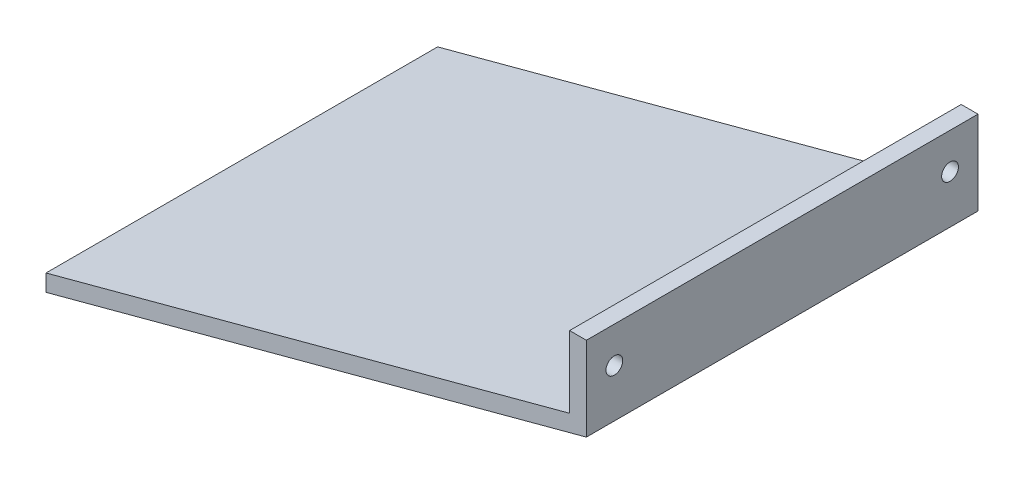
SolidWorks part; units mm, degrees
ref_plane "前视基准面" through (0, 0, 0) normal (0, 0, 1) x (1, 0, 0)
ref_plane "上视基准面" through (0, 0, 0) normal (0, 1, 0) x (1, 0, 0)
ref_plane "右视基准面" through (0, 0, 0) normal (1, 0, 0) x (0, 0, -1)
sketch "草图1" plane through (0, 0, 0) normal (0, 0, 1) x (1, 0, 0)
  line L0 (47.6587, 6.2379) -> (-48.9338, -19.644)
  line L1 (-48.9338, -19.644) -> (-48.9338, -16.644)
  line L2 (-48.9338, -16.644) -> (44.6587, 8.434)
  line L3 (47.6587, 9.2379) -> (47.6587, 6.2379)
  line L4 (47.6587, 9.2379) -> (47.6587, 21.2379)
  line L5 (44.6587, 21.2379) -> (44.6587, 8.434)
  line L6 (44.6587, 21.2379) -> (47.6587, 21.2379)
extrude "凸台-拉伸1" add sketch "草图1" along normal blind 70
sketch "草图2" plane through (44.6587, 0, 0) normal (-1, 0, 0) x (0, 0, 1)
  line L0 (0, 21.2379) -> (0, 8.434) construction
  line L1 (70, 21.2379) -> (70, 8.434) construction
  circle A0 centre (5, 14.836) radius 1.5
  circle A1 centre (65, 14.836) radius 1.5
  point P2 (0, 14.836)
  point P7 (70, 14.836)
  dimension "D2" = 3
  dimension "D3" = 3
  dimension "D1" = 5
  dimension "D4" = 5
extrude "切除-拉伸1" cut sketch "草图2" against normal up to next
